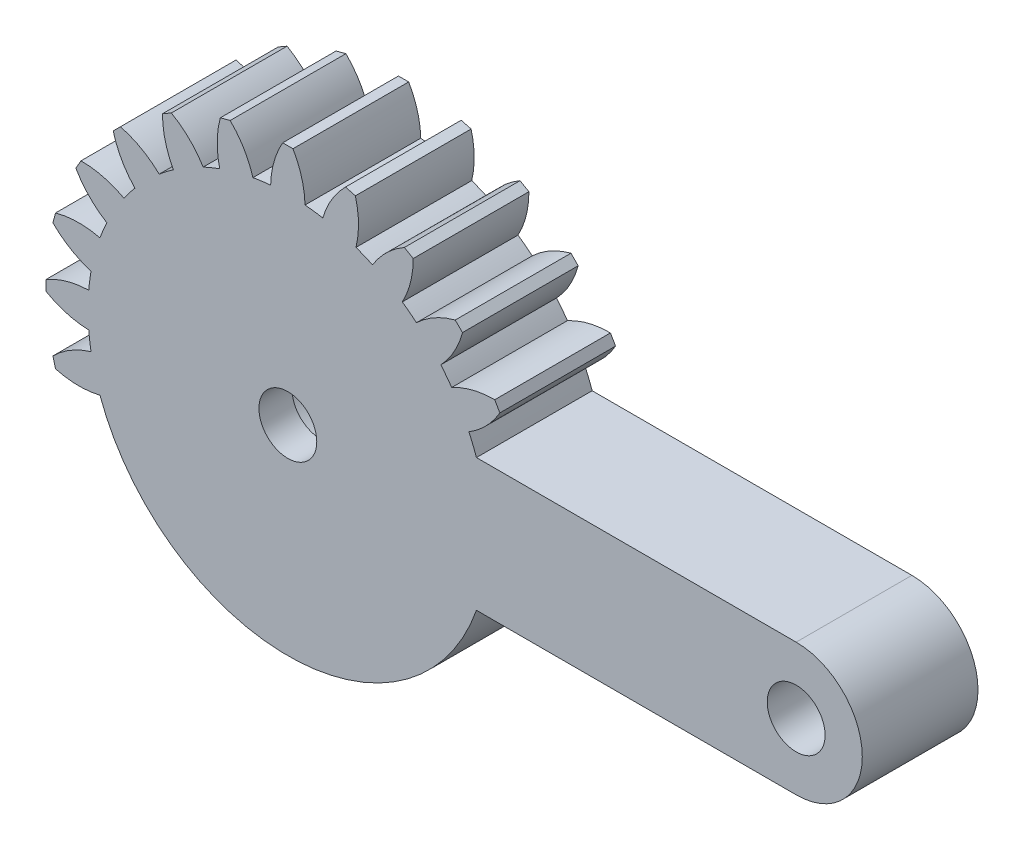
SolidWorks part; units mm, degrees
material "PLA"
ref_plane "Front Plane" through (0, 0, 0) normal (0, 0, 1) x (1, 0, 0)
ref_plane "Top Plane" through (0, 0, 0) normal (0, 1, 0) x (1, 0, 0)
ref_plane "Right Plane" through (0, 0, 0) normal (1, 0, 0) x (0, 0, -1)
sketch "Sketch1" plane through (0, 0, 0) normal (0, 0, 1) x (1, 0, 0)
  line L0 (0, 0) -> (30.75, 0) construction
  line L1 (0, 14.63) -> (0, -14.63) construction
  line L2 (-0.31, 14.63) -> (0.31, 14.63)
  line L3 (3.4871, 14.2117) -> (4.086, 14.0513)
  line L4 (7.0465, 12.825) -> (7.5835, 12.515)
  line L5 (10.1258, 10.5642) -> (10.5642, 10.1258)
  line L6 (12.515, 7.5835) -> (12.825, 7.0465)
  line L7 (14.0513, 4.086) -> (14.2117, 3.4871)
  line L8 (14.63, 0.31) -> (14.63, -0.31)
  line L9 (14.2117, -3.4871) -> (14.0513, -4.086)
  line L10 (12.825, -7.0465) -> (12.515, -7.5835)
  line L11 (10.5642, -10.1258) -> (10.1258, -10.5642)
  line L12 (7.5835, -12.515) -> (7.0465, -12.825)
  line L13 (4.086, -14.0513) -> (3.4871, -14.2117)
  line L14 (0.31, -14.63) -> (-0.31, -14.63)
  line L15 (-3.4871, -14.2117) -> (-4.086, -14.0513)
  line L16 (-7.0465, -12.825) -> (-7.5835, -12.515)
  line L17 (-10.1258, -10.5642) -> (-10.5642, -10.1258)
  line L18 (-12.515, -7.5835) -> (-12.825, -7.0465)
  line L19 (-14.0513, -4.086) -> (-14.2117, -3.4871)
  line L20 (-14.63, -0.31) -> (-14.63, 0.31)
  line L21 (-14.2117, 3.4871) -> (-14.0513, 4.086)
  line L22 (-12.825, 7.0465) -> (-12.515, 7.5835)
  line L23 (-10.5642, 10.1258) -> (-10.1258, 10.5642)
  line L24 (-7.5835, 12.515) -> (-7.0465, 12.825)
  line L25 (-4.086, 14.0513) -> (-3.4871, 14.2117)
  line L26 (30.75, 4) -> (30.75, -4) construction
  line L27 (30.75, 4) -> (11.4091, 4)
  line L28 (30.75, -4) -> (11.4091, -4)
  circle A0 centre (0, 0) radius 1.75
  circle A1 centre (0, 0) radius 12.09
  circle A2 centre (30.75, 0) radius 1.75
  arc A3 (-1.04, 12.0452) -> (-0.31, 14.63) centre (4.3585, 11.9161) cw
  arc A4 (1.04, 12.0452) -> (0.31, 14.63) centre (-4.3585, 11.9161) ccw
  arc A5 (4.1221, 11.3656) -> (4.086, 14.0513) centre (-1.1258, 12.6381) ccw
  arc A6 (2.113, 11.9039) -> (3.4871, 14.2117) centre (7.294, 10.382) cw
  arc A7 (6.9233, 9.9114) -> (7.5835, 12.515) centre (2.1835, 12.4988) ccw
  arc A8 (5.1219, 10.9514) -> (7.0465, 12.825) centre (9.7326, 8.1404) cw
  arc A9 (9.2526, 7.7818) -> (10.5642, 10.1258) centre (5.344, 11.5078) ccw
  arc A10 (7.7818, 9.2526) -> (10.1258, 10.5642) centre (11.5078, 5.344) cw
  arc A11 (10.9514, 5.1219) -> (12.825, 7.0465) centre (8.1404, 9.7326) ccw
  arc A12 (9.9114, 6.9233) -> (12.515, 7.5835) centre (12.4988, 2.1835) cw
  arc A13 (11.9039, 2.113) -> (14.2117, 3.4871) centre (10.382, 7.294) ccw
  arc A14 (11.3656, 4.1221) -> (14.0513, 4.086) centre (12.6381, -1.1258) cw
  arc A15 (12.0452, -1.04) -> (14.63, -0.31) centre (11.9161, 4.3585) ccw
  arc A16 (12.0452, 1.04) -> (14.63, 0.31) centre (11.9161, -4.3585) cw
  arc A17 (11.3656, -4.1221) -> (14.0513, -4.086) centre (12.6381, 1.1258) ccw
  arc A18 (11.9039, -2.113) -> (14.2117, -3.4871) centre (10.382, -7.294) cw
  arc A19 (9.9114, -6.9233) -> (12.515, -7.5835) centre (12.4988, -2.1835) ccw
  arc A20 (10.9514, -5.1219) -> (12.825, -7.0465) centre (8.1404, -9.7326) cw
  arc A21 (7.7818, -9.2526) -> (10.1258, -10.5642) centre (11.5078, -5.344) ccw
  arc A22 (9.2526, -7.7818) -> (10.5642, -10.1258) centre (5.344, -11.5078) cw
  arc A23 (5.1219, -10.9514) -> (7.0465, -12.825) centre (9.7326, -8.1404) ccw
  arc A24 (6.9233, -9.9114) -> (7.5835, -12.515) centre (2.1835, -12.4988) cw
  arc A25 (2.113, -11.9039) -> (3.4871, -14.2117) centre (7.294, -10.382) ccw
  arc A26 (4.1221, -11.3656) -> (4.086, -14.0513) centre (-1.1258, -12.6381) cw
  arc A27 (-1.04, -12.0452) -> (-0.31, -14.63) centre (4.3585, -11.9161) ccw
  arc A28 (1.04, -12.0452) -> (0.31, -14.63) centre (-4.3585, -11.9161) cw
  arc A29 (-4.1221, -11.3656) -> (-4.086, -14.0513) centre (1.1258, -12.6381) ccw
  arc A30 (-2.113, -11.9039) -> (-3.4871, -14.2117) centre (-7.294, -10.382) cw
  arc A31 (-6.9233, -9.9114) -> (-7.5835, -12.515) centre (-2.1835, -12.4988) ccw
  arc A32 (-5.1219, -10.9514) -> (-7.0465, -12.825) centre (-9.7326, -8.1404) cw
  arc A33 (-9.2526, -7.7818) -> (-10.5642, -10.1258) centre (-5.344, -11.5078) ccw
  arc A34 (-7.7818, -9.2526) -> (-10.1258, -10.5642) centre (-11.5078, -5.344) cw
  arc A35 (-10.9514, -5.1219) -> (-12.825, -7.0465) centre (-8.1404, -9.7326) ccw
  arc A36 (-9.9114, -6.9233) -> (-12.515, -7.5835) centre (-12.4988, -2.1835) cw
  arc A37 (-11.9039, -2.113) -> (-14.2117, -3.4871) centre (-10.382, -7.294) ccw
  arc A38 (-11.3656, -4.1221) -> (-14.0513, -4.086) centre (-12.6381, 1.1258) cw
  arc A39 (-12.0452, 1.04) -> (-14.63, 0.31) centre (-11.9161, -4.3585) ccw
  arc A40 (-12.0452, -1.04) -> (-14.63, -0.31) centre (-11.9161, 4.3585) cw
  arc A41 (-11.3656, 4.1221) -> (-14.0513, 4.086) centre (-12.6381, -1.1258) ccw
  arc A42 (-11.9039, 2.113) -> (-14.2117, 3.4871) centre (-10.382, 7.294) cw
  arc A43 (-9.9114, 6.9233) -> (-12.515, 7.5835) centre (-12.4988, 2.1835) ccw
  arc A44 (-10.9514, 5.1219) -> (-12.825, 7.0465) centre (-8.1404, 9.7326) cw
  arc A45 (-7.7818, 9.2526) -> (-10.1258, 10.5642) centre (-11.5078, 5.344) ccw
  arc A46 (-9.2526, 7.7818) -> (-10.5642, 10.1258) centre (-5.344, 11.5078) cw
  arc A47 (-5.1219, 10.9514) -> (-7.0465, 12.825) centre (-9.7326, 8.1404) ccw
  arc A48 (-6.9233, 9.9114) -> (-7.5835, 12.515) centre (-2.1835, 12.4988) cw
  arc A49 (-2.113, 11.9039) -> (-3.4871, 14.2117) centre (-7.294, 10.382) ccw
  arc A50 (-4.1221, 11.3656) -> (-4.086, 14.0513) centre (1.1258, 12.6381) cw
  arc A51 (30.75, -4) -> (30.75, 4) centre (30.75, 0) ccw
  point P10 (0, 0)
  point P156 (0, 0)
  point P159 (30.75, 0)
  dimension "D2" = 3.5
  dimension "D3" = 24.18
  dimension "D5" = 5.4
  dimension "D9" = 8
  dimension "D1" = 30.75
  dimension "D4" = 29.26
  dimension "D6" = 0.31
  dimension "D7" = 1.04
  dimension "D8" = 24
extrude "Boss-Extrude2" add sketch "Sketch1" along normal blind 7 contours A1 | A46 A1 A45 L23 | A48 A1 A47 L24 | A50 A1 A49 L25 | A1 A4 L2 A3 | A6 A1 A5 L3 | A8 A1 A7 L4 | A10 A1 A9 L5 | A12 A1 A11 L6 | A1 A13 L7 L27 | L28 A51 L27 L7 A13 A1 A16 L8 A15 A18 L9 A2 | A16 A1 A15 L8 | A18 A1 L28 L9 | A44 A1 A43 L22 | A42 A1 A41 L21 | A40 A1 A39 L20 | A38 A1 A37 L19
sketch "Sketch2" plane through (0, 0, 7) normal (0, 0, 1) x (1, 0, 0)
  line L0 (-4.5, 0) -> (4.5, 0)
  circle A2 centre (0, 0) radius 3.5
  point P4 (0, 0)
  dimension "D4" = 7
  dimension "D1" = 9
extrude "Cut-Extrude1" cut sketch "Sketch2" against normal through all
sketch "Sketch3" plane through (0, 0, 7) normal (0, 0, 1) x (1, 0, 0)
  circle A0 centre (0, 0) radius 3.5
  circle A1 centre (0, 0) radius 1.75
  dimension "D1" = 3.5
  dimension "D2" = 7
extrude "Boss-Extrude3" add sketch "Sketch3" against normal blind 2
